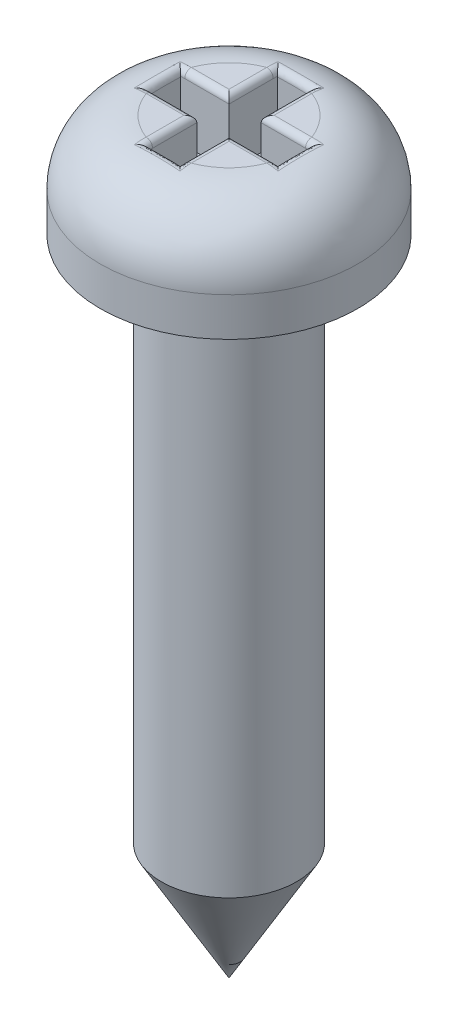
SolidWorks part; units mm, degrees
ref_plane "Front Plane" through (0, 0, 0) normal (0, 0, 1) x (1, 0, 0)
ref_plane "Top Plane" through (0, 0, 0) normal (0, 1, 0) x (1, 0, 0)
ref_plane "Right Plane" through (0, 0, 0) normal (1, 0, 0) x (0, 0, -1)
sketch "Sketch1" plane through (0, 0, 0) normal (0, 1, 0) x (1, 0, 0)
  circle A0 centre (0, 0) radius 2
  dimension "D1" = 4
extrude "Boss-Extrude1" add sketch "Sketch1" along normal blind 0.6
sketch "Sketch3" plane through (0, 0.6, 0) normal (0, 1, 0) x (1, 0, 0)
  circle A0 centre (0, 0) radius 2
  dimension "D1" = 4
extrude "Boss-Extrude2" add sketch "Sketch3" along normal blind 1
fillet "Fillet1" radius 1 1 edges at (0, 1.6, 2)
sketch "Sketch4" plane through (0, 1.6, 0) normal (0, 1, 0) x (1, 0, 0)
  line L0 (-1, 0) -> (1, 0) construction
  line L1 (0, 1) -> (0, -1) construction
  line L2 (-1, -0.25) -> (-0.25, -0.25)
  line L3 (-0.25, 1) -> (-0.25, 0.25)
  line L4 (-1, 0.25) -> (-0.25, 0.25)
  line L5 (0.25, 1) -> (0.25, 0.25)
  line L6 (0.25, 1) -> (-0.25, 1)
  line L7 (0.25, -1) -> (-0.25, -1)
  line L8 (1, 0.25) -> (1, -0.25)
  line L9 (-1, 0.25) -> (-1, -0.25)
  line L10 (0.25, 0.25) -> (1, 0.25)
  line L11 (-1, 0.25) -> (1, 0.25) construction
  line L12 (0.25, -0.25) -> (0.25, -1)
  line L13 (0.25, 1) -> (0.25, -1) construction
  line L14 (0.25, -0.25) -> (1, -0.25)
  line L15 (-1, -0.25) -> (1, -0.25) construction
  line L16 (-0.25, -0.25) -> (-0.25, -1)
  line L17 (-0.25, 1) -> (-0.25, -1) construction
  point P4 (0, 0)
  point P10 (0, 0)
  dimension "D1" = 2
  dimension "D2" = 2
  dimension "D3" = 0.25
  dimension "D4" = 0.25
extrude "Cut-Extrude1" cut sketch "Sketch4" against normal blind 1
fillet "Fillet2" radius 0.1 20 edges at (0.25, 1.6, -0.6091) (-0.25, 1.6, 0.6091) (0.6091, 1.6, -0.25) (0.6091, 1.6, 0.25) (0.25, 1.6, 0.6091) (-0.6091, 1.6, 0.25) (-0.6091, 1.6, -0.25) (-0.25, 1.6, -0.6091)
sketch "Sketch5" plane through (0, 0, 0) normal (0, -1, 0) x (1, 0, 0)
  circle A0 centre (0, 0) radius 1.05
  dimension "D1" = 2.1
extrude "Boss-Extrude3" add sketch "Sketch5" along normal blind 10
chamfer "Chamfer1" distance 1.05 angle 60 1 edges at (0, -10, -1.05)
